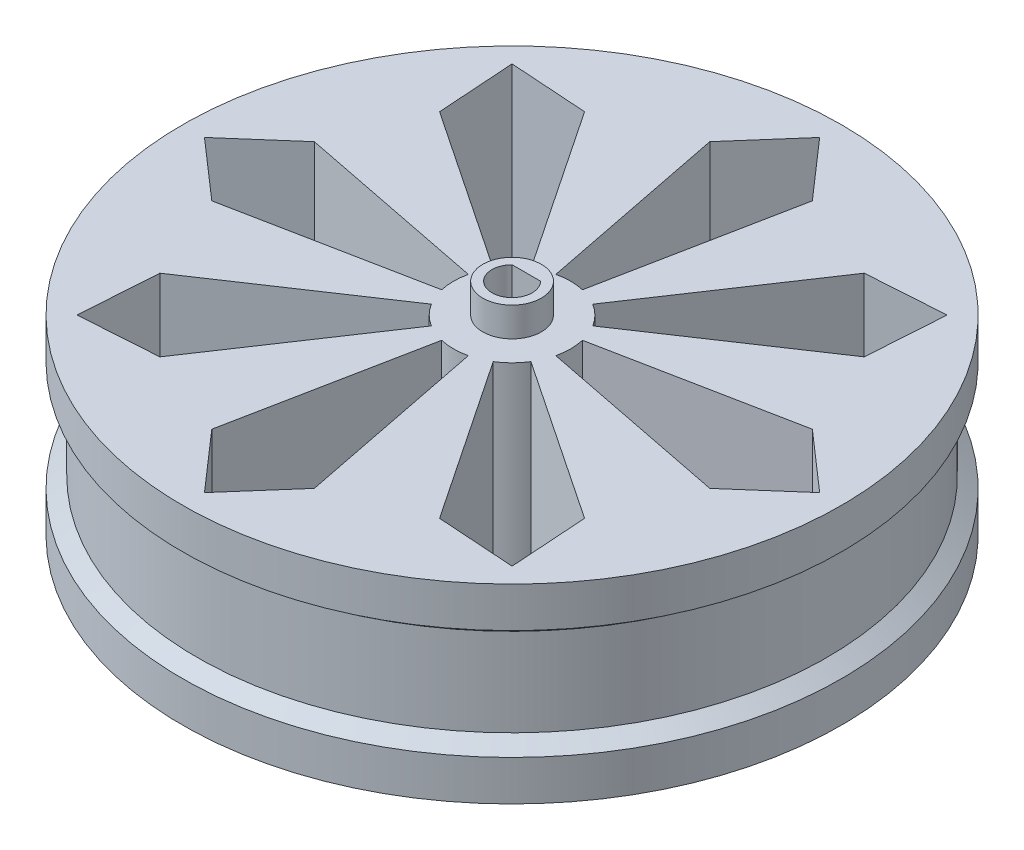
SolidWorks part; units mm, degrees
ref_plane "Front Plane" through (0, 0, 0) normal (0, 0, 1) x (1, 0, 0)
ref_plane "Top Plane" through (0, 0, 0) normal (0, 1, 0) x (1, 0, 0)
ref_plane "Right Plane" through (0, 0, 0) normal (1, 0, 0) x (0, 0, -1)
sketch "Sketch1" plane through (0, 0, 0) normal (0, 1, 0) x (1, 0, 0)
  circle A0 centre (0, 0) radius 45
  dimension "D1" = 90
extrude "Boss-Extrude1" add sketch "Sketch1" along normal blind 26
sketch "Sketch2" plane through (0, 26, 0) normal (0, 1, 0) x (1, 0, 0)
  circle A0 centre (0, 0) radius 4
  dimension "D1" = 8
extrude "Boss-Extrude2" add sketch "Sketch2" along normal blind 4
sketch "Sketch4" plane through (0, 26, 0) normal (0, 1, 0) x (1, 0, 0)
  line L0 (0, 0) -> (0, 48.9542) construction
  line L1 (0, 0) -> (51.2441, 0) construction
  line L3 (-1.8184, 7.7906) -> (-7, 34)
  line L5 (7, 34) -> (1.8184, 7.7906)
  line L7 (-7, 34) -> (0, 42)
  line L8 (0, 42) -> (7, 34)
  line L9 (4.223, 6.7946) -> (19.0919, 28.9914)
  line L10 (19.0919, 28.9914) -> (29.6985, 29.6985)
  line L11 (29.6985, 29.6985) -> (28.9914, 19.0919)
  line L12 (28.9914, 19.0919) -> (6.7946, 4.223)
  line L13 (7.7906, 1.8184) -> (34, 7)
  line L14 (34, 7) -> (42, 0)
  line L15 (42, 0) -> (34, -7)
  line L16 (34, -7) -> (7.7906, -1.8184)
  line L17 (6.7946, -4.223) -> (28.9914, -19.0919)
  line L18 (28.9914, -19.0919) -> (29.6985, -29.6985)
  line L19 (29.6985, -29.6985) -> (19.0919, -28.9914)
  line L20 (19.0919, -28.9914) -> (4.223, -6.7946)
  line L21 (1.8184, -7.7906) -> (7, -34)
  line L22 (7, -34) -> (0, -42)
  line L23 (0, -42) -> (-7, -34)
  line L24 (-7, -34) -> (-1.8184, -7.7906)
  line L25 (-4.223, -6.7946) -> (-19.0919, -28.9914)
  line L26 (-19.0919, -28.9914) -> (-29.6985, -29.6985)
  line L27 (-29.6985, -29.6985) -> (-28.9914, -19.0919)
  line L28 (-28.9914, -19.0919) -> (-6.7946, -4.223)
  line L29 (-7.7906, -1.8184) -> (-34, -7)
  line L30 (-34, -7) -> (-42, 0)
  line L31 (-42, 0) -> (-34, 7)
  line L32 (-34, 7) -> (-7.7906, 1.8184)
  line L33 (-6.7946, 4.223) -> (-28.9914, 19.0919)
  line L34 (-28.9914, 19.0919) -> (-29.6985, 29.6985)
  line L35 (-29.6985, 29.6985) -> (-19.0919, 28.9914)
  line L36 (-19.0919, 28.9914) -> (-4.223, 6.7946)
  arc A1 (1.8184, 7.7906) -> (-1.8184, 7.7906) centre (0, 0) ccw
  arc A2 (6.7946, 4.223) -> (4.223, 6.7946) centre (0, 0) ccw
  arc A3 (7.7906, -1.8184) -> (7.7906, 1.8184) centre (0, 0) ccw
  arc A4 (4.223, -6.7946) -> (6.7946, -4.223) centre (0, 0) ccw
  arc A5 (-1.8184, -7.7906) -> (1.8184, -7.7906) centre (0, 0) ccw
  arc A6 (-6.7946, -4.223) -> (-4.223, -6.7946) centre (0, 0) ccw
  arc A7 (-7.7906, 1.8184) -> (-7.7906, -1.8184) centre (0, 0) ccw
  arc A8 (-4.223, 6.7946) -> (-6.7946, 4.223) centre (0, 0) ccw
  point P9 (1.8184, 7.7906)
  point P46 (0, 0)
  dimension "D4" = 8
  dimension "D2" = 14
  dimension "D3" = 8
  dimension "D1" = 42
  dimension "D5" = 8
extrude "Cut-Extrude2" cut sketch "Sketch4" against normal through all
sketch "Sketch5" plane through (0, 26, 0) normal (0, 1, 0) x (1, 0, 0)
  line L0 (9.7943, 33.6359) -> (8.5715, 20.6935)
  line L1 (8.5715, 20.6935) -> (16.8585, 30.7098)
  line L2 (0, 0) -> (13.7766, 33.2597) construction
  line L3 (13.7766, 33.2597) -> (29.6985, 29.6985) construction
  line L4 (13.7766, 33.2597) -> (0, 42) construction
  line L5 (30.7098, 16.8585) -> (20.6935, 8.5715)
  line L6 (20.6935, 8.5715) -> (33.6359, 9.7943)
  line L7 (33.6359, -9.7943) -> (20.6935, -8.5715)
  line L8 (20.6935, -8.5715) -> (30.7098, -16.8585)
  line L9 (16.8585, -30.7098) -> (8.5715, -20.6935)
  line L10 (8.5715, -20.6935) -> (9.7943, -33.6359)
  line L11 (-9.7943, -33.6359) -> (-8.5715, -20.6935)
  line L12 (-8.5715, -20.6935) -> (-16.8585, -30.7098)
  line L13 (-30.7098, -16.8585) -> (-20.6935, -8.5715)
  line L14 (-20.6935, -8.5715) -> (-33.6359, -9.7943)
  line L15 (-33.6359, 9.7943) -> (-20.6935, 8.5715)
  line L16 (-20.6935, 8.5715) -> (-30.7098, 16.8585)
  line L17 (-16.8585, 30.7098) -> (-8.5715, 20.6935)
  line L18 (-8.5715, 20.6935) -> (-9.7943, 33.6359)
  arc A0 (16.8585, 30.7098) -> (9.7943, 33.6359) centre (13.7766, 33.2597) ccw
  arc A1 (33.6359, 9.7943) -> (30.7098, 16.8585) centre (33.2597, 13.7766) ccw
  arc A2 (30.7098, -16.8585) -> (33.6359, -9.7943) centre (33.2597, -13.7766) ccw
  arc A3 (9.7943, -33.6359) -> (16.8585, -30.7098) centre (13.7766, -33.2597) ccw
  arc A4 (-16.8585, -30.7098) -> (-9.7943, -33.6359) centre (-13.7766, -33.2597) ccw
  arc A5 (-33.6359, -9.7943) -> (-30.7098, -16.8585) centre (-33.2597, -13.7766) ccw
  arc A6 (-30.7098, 16.8585) -> (-33.6359, 9.7943) centre (-33.2597, 13.7766) ccw
  arc A7 (-9.7943, 33.6359) -> (-16.8585, 30.7098) centre (-13.7766, 33.2597) ccw
  point P41 (0, 0)
  dimension "D2" = 4
  dimension "D1" = 13
  dimension "D3" = 36
  dimension "D4" = 8
extrude "Cut-Extrude3" [suppressed] cut sketch "Sketch5" against normal through all
sketch "Sketch6" plane through (0, 0, 0) normal (1, 0, 0) x (0, 0, -1)
  line L0 (45, 13) -> (-45, 13) construction
  line L1 (45, 0) -> (45, 26) construction
  line L2 (-45, 26) -> (-45, 0) construction
  line L3 (-45, 20.5) -> (-43, 19)
  line L4 (-43, 19) -> (-43, 13)
  line L5 (-43, 13) -> (-43, 7)
  line L6 (-43, 7) -> (-45, 5.5)
  line L7 (-45, 5.5) -> (-45, 20.5)
  line L8 (0, 0) -> (0, 41.7722) construction
  dimension "D1" = 6
  dimension "D2" = 15
  dimension "D3" = 2
revolve "Cut-Revolve4" cut sketch "Sketch6" angle 360 about L8
chamfer "Chamfer2" [suppressed] distance 2 angle 45
chamfer "Chamfer3" [suppressed] distance 2 angle 45
chamfer "Chamfer4" [suppressed] distance 2 angle 45
chamfer "Chamfer5" [suppressed] distance 2 angle 45
fillet "Fillet2" [suppressed] radius 2
sketch "Sketch8" [suppressed] plane through (0, 0, 0) normal (0, 0, 1) x (1, 0, 0)
  line L0 (43, 13) -> (-43, 13) construction
  line L1 (43, 7) -> (43, 19) construction
  line L2 (-43, 19) -> (-43, 7) construction
  line L3 (-48.1, 26) -> (-48.1, 18.95)
  line L4 (-43, 7) -> (-45, 5.5) construction
  line L5 (-45, 20.5) -> (-43, 19) construction
  line L6 (-45, 25.9755) -> (-45, 20.5) construction
  line L7 (-45, 5.5) -> (-45, 0) construction
  line L8 (-43, 7) -> (-45, 5.5) construction
  line L9 (-43, 19) -> (-43, 7) construction
  line L10 (-45, 20.5) -> (-43, 19) construction
  line L11 (-45, 26) -> (-45, 20.5) construction
  line L12 (-45.1, 26) -> (-45.1, 20.45)
  line L13 (-45.1, 20.45) -> (-43.1, 18.95)
  line L14 (-43.1, 18.95) -> (-43.1, 7.05)
  line L15 (-43.1, 7.05) -> (-45.1, 5.55)
  line L16 (-45.1, 5.55) -> (-45.1, 0)
  line L17 (-45.1, 26) -> (-45, 26.1)
  line L18 (-45, 26.1) -> (-43, 26.1)
  line L19 (-45, 5.5) -> (-45, 0.0245) construction
  line L20 (-45, 26) -> (-45, 20.5) construction
  line L21 (-31.8428, 26) -> (-45, 26) construction
  line L22 (-45.1, 5.55) -> (-45.1, 0.0245) construction
  line L23 (-45.1, 0) -> (-45, -0.1)
  line L24 (-45, -0.1) -> (-43, -0.1)
  line L25 (-48.1, 18.95) -> (-46.1, 17.45) construction
  line L26 (-46.1, 17.45) -> (-46.1, 8.55) construction
  line L27 (-46.1, 8.55) -> (-48.1, 7.05) construction
  line L28 (-48.1, 7.05) -> (-48.1, 0)
  line L29 (-48.1, 26) -> (-47, 27.1)
  line L30 (-47, 27.1) -> (-43, 27.1)
  line L31 (-43, 27.1) -> (-43, 26.1)
  line L32 (-48.1, 0) -> (-47, -1.1)
  line L33 (-47, -1.1) -> (-43, -1.1)
  line L34 (-43, -1.1) -> (-43, -0.1)
  line L35 (0, 0.0245) -> (0, 44.103) construction
  line L36 (-48.1, 18.95) -> (-48.1, 7.05)
  dimension "D2" = 0.1
  dimension "D3" = 2
  dimension "D4" = 0.1
  dimension "D5" = 2
  dimension "D7" = 1
  dimension "D8" = 1
  dimension "D1" = 0.1
  dimension "D6" = 3
revolve "Revolve1" [suppressed] add sketch "Sketch8" angle 360 about L35
sketch "Sketch9" plane through (0, 30, 0) normal (0, 1, 0) x (1, 0, 0)
  line L0 (-1.9391, 1.95) -> (1.9391, 1.95)
  line L1 (0, 0) -> (0, -2.75) construction
  arc A0 (-1.9391, 1.95) -> (1.9391, 1.95) centre (0, 0) ccw
  point P6 (0, 1.95)
  dimension "D1" = 5.5
  dimension "D2" = 4.7
extrude "Cut-Extrude4" cut sketch "Sketch9" against normal blind 22
